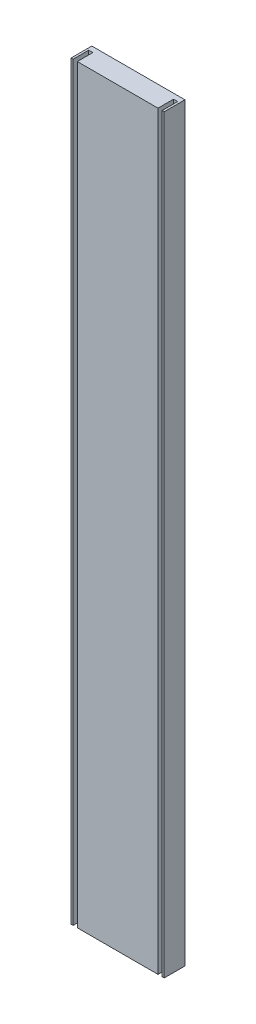
SolidWorks part; units mm, degrees
ref_plane "Спереди" through (0, 0, 0) normal (0, 0, 1) x (1, 0, 0)
ref_plane "Сверху" through (0, 0, 0) normal (0, 1, 0) x (1, 0, 0)
ref_plane "Справа" through (0, 0, 0) normal (1, 0, 0) x (0, 0, -1)
sketch "Эскиз1" plane through (0, 0, 0) normal (0, 1, 0) x (1, 0, 0)
  line L0 (-31.6163, -7.2411) -> (-31.6163, 7.7589)
  line L1 (-33.6163, 12.7589) -> (56.3837, 12.7589)
  line L2 (-33.6163, 12.7589) -> (-33.6163, -7.2411)
  line L3 (-33.6163, -7.2411) -> (-31.6163, -7.2411)
  line L4 (56.3837, 12.7589) -> (56.3837, -7.2411)
  line L5 (-31.6163, 7.7589) -> (-27.6163, 7.7589)
  line L6 (-27.6163, 7.7589) -> (-27.6163, -7.2411)
  line L7 (54.3837, -7.2411) -> (54.3837, 7.7589)
  line L8 (54.3837, 7.7589) -> (50.3837, 7.7589)
  line L9 (50.3837, 7.7589) -> (50.3837, -7.2411)
  line L10 (-27.6163, -7.2411) -> (50.3837, -7.2411)
  line L11 (54.3837, -7.2411) -> (56.3837, -7.2411)
  dimension "D1" = 90
  dimension "D2" = 20
  dimension "D3" = 4
  dimension "D4" = 4
  dimension "D5" = 2
  dimension "D6" = 2
  dimension "D7" = 15
  dimension "D8" = 15
extrude "Бобышка-Вытянуть1" add sketch "Эскиз1" along normal blind 50 and the other way up to surface (675 mm away)
